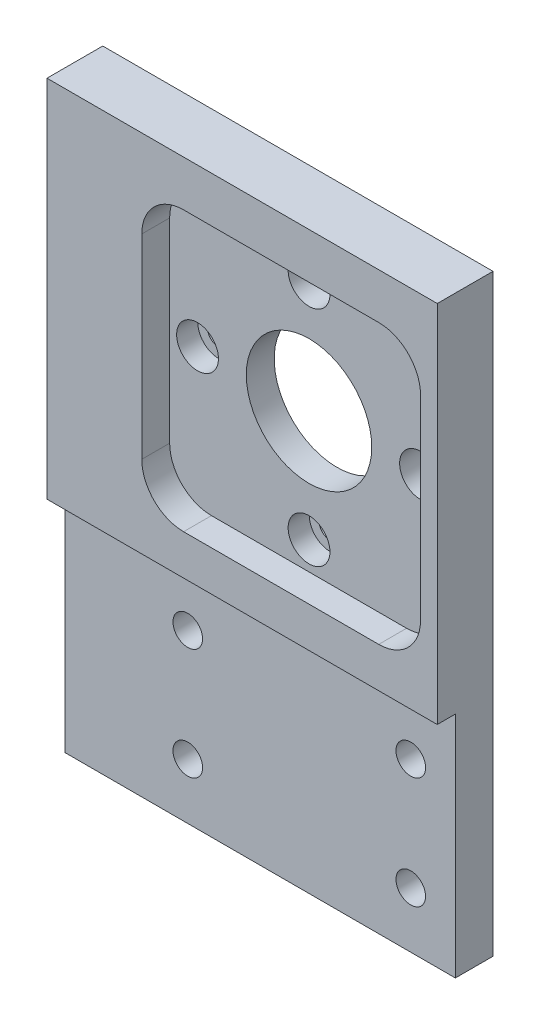
SolidWorks part; units mm, degrees
material "1060 Alloy"
ref_plane "Front Plane" through (0, 0, 0) normal (0, 0, 1) x (1, 0, 0)
ref_plane "Top Plane" through (0, 0, 0) normal (0, 1, 0) x (1, 0, 0)
ref_plane "Right Plane" through (0, 0, 0) normal (1, 0, 0) x (0, 0, -1)
sketch "Sketch1" plane through (0, 0, 0) normal (0, 0, 1) x (1, 0, 0)
  line L1 (0, 0) -> (88.9, 0)
  line L2 (0, 0) -> (0, -135.128)
  line L3 (0, -135.128) -> (88.9, -135.128)
  line L4 (88.9, 0) -> (88.9, -135.128)
  dimension "D1" = 135.128
  dimension "D2" = 88.9
extrude "Boss-Extrude1" add sketch "Sketch1" along normal blind 12.7
sketch "Sketch2" plane through (0, 0, 12.7) normal (0, 0, 1) x (1, 0, 0)
  line L0 (88.9, -135.128) -> (88.9, 0) construction
  line L2 (88.9, 0) -> (0, 0) construction
  circle A0 centre (53.34, -42.164) radius 14.2875
  dimension "D3" = 28.575
  dimension "D2" = 42.164
  dimension "D1" = 35.56
extrude "Cut-Extrude1" cut sketch "Sketch2" against normal through all
hole_wizard "CBORE for #10 Socket Head Cap Screw1" positions "Sketch3" profile "Sketch4" counterbore size "#10" standard "ANSI Inch" end condition through all
sketch "Sketch3" plane through (0, 0, 12.7) normal (0, 0, 1) x (1, 0, 0)
  line L0 (53.34, -16.764) -> (53.34, -67.564) construction
  line L2 (27.94, -42.164) -> (78.74, -42.164) construction
  circle A0 centre (53.34, -42.164) radius 14.2875 construction
  point P2 (53.34, -16.764)
  point P6 (53.34, -67.564)
  point P29 (53.34, -42.164)
  point P32 (27.94, -42.164)
  point P34 (78.74, -42.164)
  point P43 (53.34, -42.164)
  dimension "D1" = 50.8
sketch "Sketch4" plane through (53.34, -16.764, 12.7) normal (1, 0, 0) x (0, -1, 0)
  line L0 (0, 0) -> (0, 12.7)
  line L1 (0, 12.7) -> (2.5527, 12.7)
  line L3 (2.5527, 12.7) -> (2.5527, 4.826)
  line L4 (2.5527, 4.826) -> (4.7625, 4.826)
  line L5 (4.7625, 4.826) -> (4.7625, 0)
  line L7 (4.7625, 0) -> (0, 0)
  line L11 (0, -6.35) -> (0, 107.95) construction
  dimension "Thru Hole Dia." = 5.1054
  dimension "Thru Hole Depth" = 12.7
  dimension "C'Bore Dia." = 9.525
  dimension "C'Bore Depth" = 4.826
sketch "Sketch5" plane through (0, 0, 12.7) normal (0, 0, 1) x (1, 0, 0)
  line L1 (0, -135.128) -> (88.9, -135.128) construction
  circle A0 centre (27.94, -122.428) radius 3.3734
  circle A1 centre (78.74, -122.428) radius 3.3734
  circle A2 centre (27.94, -97.028) radius 3.3734
  circle A3 centre (78.74, -97.028) radius 3.3734
  circle A4 centre (53.34, -42.164) radius 14.2875 construction
  point P8 (0, 0)
  point P10 (0, 0)
  point P12 (63.5, -96.52)
  point P13 (63.5, -121.92)
  dimension "D1" = 50.8
  dimension "D2" = 25.4
  dimension "D3" = 12.7
  dimension "D4" = 25.4
  dimension "D5" = 6.7469
extrude "Cut-Extrude2" cut sketch "Sketch5" against normal through all contours A1 | A0 | A3 | A2
sketch "Sketch6" plane through (0, 0, 12.7) normal (0, 0, 1) x (1, 0, 0)
  line L6 (21.59, -73.914) -> (85.09, -73.914)
  line L7 (21.59, -73.914) -> (21.59, -10.414)
  line L8 (21.59, -10.414) -> (85.09, -10.414)
  line L9 (85.09, -73.914) -> (85.09, -10.414)
  line L10 (21.59, -73.914) -> (85.09, -10.414) construction
  line L11 (21.59, -10.414) -> (85.09, -73.914) construction
  point P7 (53.34, -42.164)
  dimension "D2" = 63.5
extrude "Cut-Extrude3" cut sketch "Sketch6" against normal blind 6.35
fillet "Fillet1" radius 9.525 4 edges at (21.59, -73.914, 9.525) (85.09, -73.914, 9.525) (85.09, -10.414, 9.525) (21.59, -10.414, 9.525)
sketch "Sketch7" plane through (0, 0, 12.7) normal (0, 0, 1) x (1, 0, 0)
  line L0 (88.9, -135.128) -> (88.9, 0) construction
  line L1 (0, -135.128) -> (88.9, -135.128)
  line L2 (0, -135.128) -> (0, -83.058)
  line L3 (0, -83.058) -> (88.9, -83.058)
  line L4 (88.9, -135.128) -> (88.9, -83.058)
  dimension "D1" = 52.07
extrude "Cut-Extrude4" cut sketch "Sketch7" against normal blind 4.1275
hole_wizard "CBORE for #10 Socket Head Cap Screw2" positions "Sketch8" profile "Sketch9" counterbore size "#10" standard "ANSI Inch"
sketch "Sketch8" plane through (0, 0, 6.35) normal (0, 0, 1) x (1, 0, 0)
  point P0 (53.34, -16.764)
  point P3 (78.74, -42.164)
  point P6 (53.34, -67.564)
  point P9 (27.94, -42.164)
sketch "Sketch9" plane through (53.34, -16.764, 6.35) normal (1, 0, 0) x (0, -1, 0)
  line L0 (0, 0) -> (0, 24.3938)
  line L1 (0, 24.3938) -> (2.5527, 22.86)
  line L2 (2.5527, 22.86) -> (2.5527, 4.826)
  line L3 (2.5527, 4.826) -> (4.7625, 4.826)
  line L4 (4.7625, 4.826) -> (4.7625, 0)
  line L5 (4.7625, 0) -> (0, 0)
  line L10 (0, 24.3938) -> (-2.5527, 22.86) construction
  line L11 (0, -6.35) -> (0, 107.95) construction
  dimension "Hole Dia." = 5.1054
  dimension "Hole Depth" = 22.86
  dimension "C'Bore Dia." = 9.525
  dimension "C'Bore Depth" = 4.826
  dimension "Drill Angle" = 118
